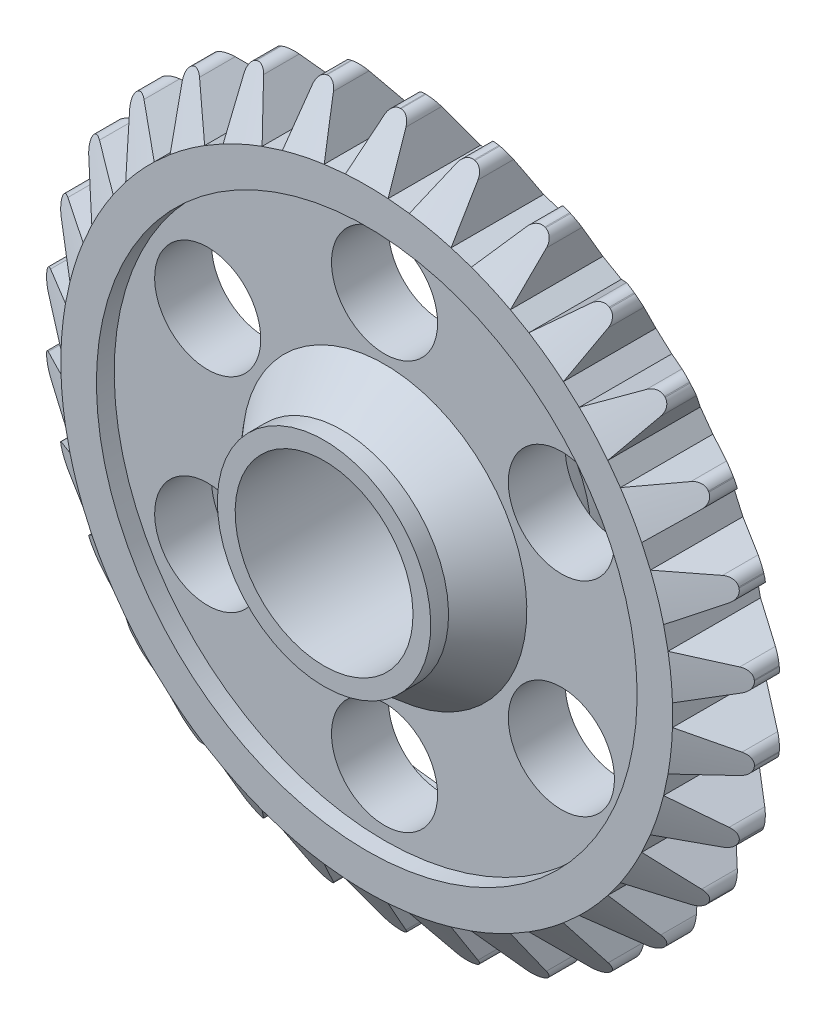
SolidWorks part; units mm, degrees
ref_plane "Спереди" through (0, 0, 0) normal (0, 0, 1) x (1, 0, 0)
ref_plane "Сверху" through (0, 0, 0) normal (0, 1, 0) x (1, 0, 0)
ref_plane "Справа" through (0, 0, 0) normal (1, 0, 0) x (0, 0, -1)
sketch "Эскиз2" plane through (0, 0, 0) normal (1, 0, 0) x (0, 0, -1)
  line L0 (-20, 0) -> (20, 0)
  line L1 (20, 0) -> (20, 25)
  line L2 (20, 25) -> (25, 25)
  line L3 (25, 25) -> (25, 30)
  line L4 (25, 30) -> (20, 30)
  line L5 (20, 30) -> (8, 40)
  line L6 (8, 40) -> (8, 76)
  line L7 (8, 76) -> (13, 76)
  line L8 (13, 76) -> (13, 86)
  line L9 (13, 86) -> (3.5, 100)
  line L10 (3.5, 100) -> (-3.5, 100)
  line L11 (0, 122.5735) -> (0, -125.0735) construction
  line L12 (-13, 86) -> (-3.5, 100)
  line L13 (-13, 76) -> (-13, 86)
  line L14 (-8, 76) -> (-13, 76)
  line L15 (-8, 40) -> (-8, 76)
  line L16 (-20, 30) -> (-8, 40)
  line L17 (-25, 30) -> (-20, 30)
  line L18 (-25, 25) -> (-25, 30)
  line L19 (-20, 25) -> (-25, 25)
  line L20 (-20, 0) -> (-20, 25)
  point P24 (0, 100)
  point P33 (0, 0)
  dimension "D1" = 20
  dimension "D2" = 25
  dimension "D3" = 5
  dimension "D4" = 5
  dimension "D5" = 3.5
  dimension "D6" = 40
  dimension "D7" = 8
  dimension "D8" = 5
  dimension "D9" = 100
  dimension "D10" = 10
  dimension "D11" = 24
revolve "Повернуть1" add sketch "Эскиз2" angle 360 about L0
sketch "Эскиз4" plane through (0, 0, 0) normal (0, 0, 1) x (1, 0, 0)
  line L0 (-109.8443, 0) -> (114.8995, 0) construction
  line L1 (-109.9477, 3) -> (-85.9477, 3)
  line L2 (-85.9477, 3) -> (-85.9477, -3)
  line L3 (-85.9477, -3) -> (-109.9477, -3)
  line L4 (-109.9477, -3) -> (-109.9477, 3)
  circle A2 centre (0, 0) radius 86 construction
  dimension "D1" = 6
  dimension "D2" = 24
revolve "Вырез-Повернуть1" cut sketch "Эскиз4" angle 180 mid plane about L2
sketch "Эскиз6" plane through (0, 0, 0) normal (1, 0, 0) x (0, 0, -1)
  line L0 (-25, 0) -> (25, 0)
  line L1 (-25, 30) -> (-25, -30) construction
  line L2 (25, -30) -> (25, 30) construction
  line L6 (-25, 0) -> (-25, 25)
  line L7 (-25, 25) -> (25, 25)
  line L8 (25, 25) -> (25, 0)
revolve "Вырез-Повернуть2" cut sketch "Эскиз6" angle 360 about L0
ref_plane "Плоскость5" through (0, 10, 0) normal (0, -1, 0) x (-1, 0, 0)
sketch "Эскиз10" plane through (0, 10, 0) normal (0, -1, 0) x (-1, 0, 0)
  line L0 (0, 7.5) -> (25, 7.5)
  line L1 (25, 7.5) -> (25, -7.5)
  line L2 (25, -7.5) -> (0, -7.5)
  line L3 (0, -7.5) -> (0, 7.5)
  line L5 (25, 0) -> (0, 0) construction
  dimension "D1" = 15
  dimension "D2" = 25
revolve "Повернуть3" add sketch "Эскиз10" angle 180 about L3
ref_plane "Плоскость6" through (0, 3, 0) normal (0, 1, 0) x (1, 0, 0)
sketch "Эскиз13" plane through (0, 3, 0) normal (0, 1, 0) x (1, 0, 0)
  line L0 (-85.9477, 13) -> (-85.9477, -13)
  line L1 (-85.9477, -13) -> (-105.9477, -13)
  line L2 (-105.9477, -13) -> (-105.9477, 13)
  line L3 (-105.9477, 13) -> (-85.9477, 13)
  dimension "D1" = 20
revolve "Вырез-Повернуть4" cut sketch "Эскиз13" angle 20 about L0
mirror "Зеркальное отражение1" about plane through (0, 0, 0) normal (0, 1, 0) of "Вырез-Повернуть4"
pattern_circular "Круговой массив30" count 30 over 360 about axis through (0, 0, 0) along (0, 0, 1) of "Зеркальное отражение1", "Вырез-Повернуть1", "Вырез-Повернуть4"
fillet "Скругление7" radius 3 60 edges at (-38.4093, 92.3294, 0) (-42.9133, 90.3241, 0) (-56.7663, 82.3261, 0) (-60.755, 79.4281, 0) (-72.6424, 68.7247, 0) (-75.9414, 65.0608, 0) (-85.3437, 52.1197, 0) (-87.8088, 47.8499, 0) (-94.315, 33.2368, 0) (-95.8385, 28.5478, 0) (-99.1643, 12.9013, 0) (-99.6796, 7.998, 0) (-99.6796, -7.998, 0) (-99.1643, -12.9013, 0) (-95.8385, -28.5478, 0) (-94.315, -33.2368, 0) (-87.8088, -47.8499, 0) (-85.3437, -52.1197, 0) (-72.6424, -68.7247, 0) (-75.9414, -65.0608, 0) (-56.7663, -82.3261, 0) (-60.755, -79.4281, 0) (-38.4093, -92.3294, 0) (-42.9133, -90.3241, 0) (-18.3736, -98.2976, 0) (-23.1961, -97.2725, 0) (-2.4651, -99.9696, 0) (2.4651, -99.9696, 0) (42.9133, -90.3241, 0) (38.4093, -92.3294, 0) (23.1961, -97.2725, 0) (18.3736, -98.2976, 0) (60.755, -79.4281, 0) (56.7663, -82.3261, 0) (75.9414, -65.0608, 0) (72.6424, -68.7247, 0) (87.8088, -47.8499, 0) (85.3437, -52.1197, 0) (95.8385, -28.5478, 0) (94.315, -33.2368, 0) (99.6796, -7.998, 0) (99.1643, -12.9013, 0) (99.6796, 7.998, 0) (99.1643, 12.9013, 0) (95.8385, 28.5478, 0) (94.315, 33.2368, 0) (87.8088, 47.8499, 0) (85.3437, 52.1197, 0) (75.9414, 65.0608, 0) (72.6424, 68.7247, 0) (60.755, 79.4281, 0) (56.7663, 82.3261, 0) (38.4093, 92.3294, 0) (42.9133, 90.3241, 0) (2.4651, 99.9696, 0) (-2.4651, 99.9696, 0) (-23.1961, 97.2725, 0) (-18.3736, 98.2976, 0) (18.3736, 98.2976, 0) (23.1961, 97.2725, 0)
sketch "Эскиз15" plane through (0, 0, 0) normal (1, 0, 0) x (0, 0, -1)
  line L0 (-13, 57.405) -> (13, 57.405)
  line L1 (-13, 61.8642) -> (-13, 52.9458) construction
  line L2 (13, 52.9458) -> (13, 61.8642) construction
  line L3 (13, 57.405) -> (13, 72.3233)
  line L4 (13, 65.8789) -> (13, 72.9329) construction
  line L5 (13, 72.3233) -> (-13, 72.3233)
  line L6 (-13, 72.9329) -> (-13, 65.8789) construction
  line L7 (-13, 72.3233) -> (-13, 57.405)
  point P6 (-13, 64.8642)
  dimension "D1" = 3
revolve "Вырез-Повернуть6" cut sketch "Эскиз15" angle 360 about L0
pattern_circular "Круговой массив31" count 6 over 360 about axis through (0, 0, 0) along (0, 0, 1) of "Вырез-Повернуть6"
